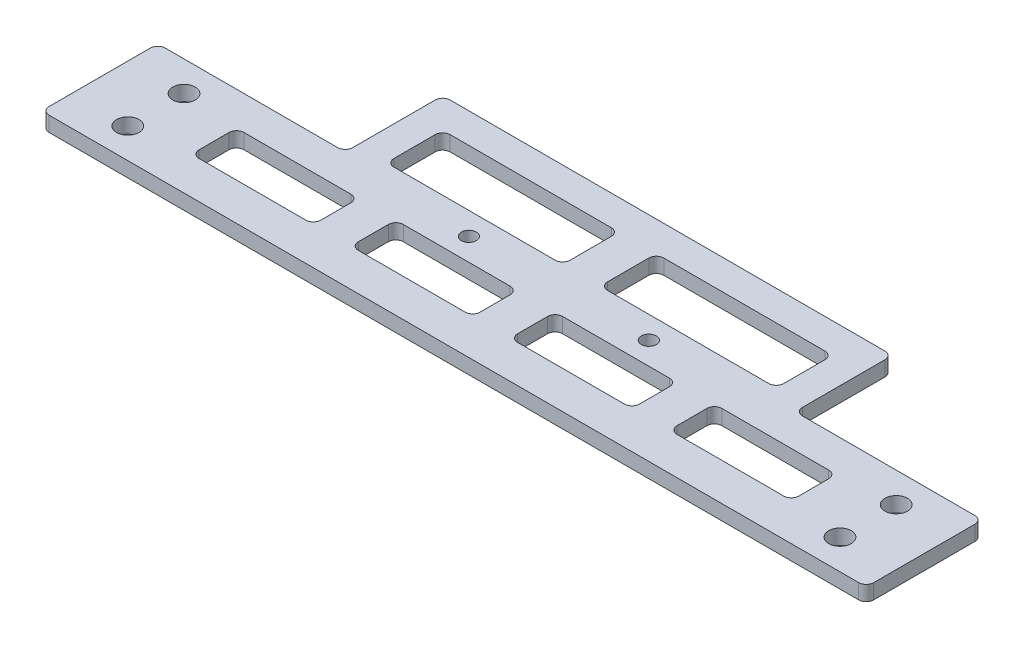
SolidWorks part; units mm, degrees
material "Thornel Mat VMA"
ref_plane "前视基准面" through (0, 0, 0) normal (0, 0, 1) x (1, 0, 0)
ref_plane "上视基准面" through (0, 0, 0) normal (0, 1, 0) x (1, 0, 0)
ref_plane "右视基准面" through (0, 0, 0) normal (1, 0, 0) x (0, 0, -1)
sketch "草图1" plane through (0, 0, 0) normal (0, 1, 0) x (1, 0, 0)
  line L0 (-47.5, 3.75) -> (47.5, -3.75) construction
  line L1 (-47.5, 3.75) -> (47.5, 3.75) construction
  line L2 (-47.5, 3.75) -> (-47.5, -3.75) construction
  line L3 (-47.5, -3.75) -> (47.5, -3.75) construction
  line L4 (47.5, 3.75) -> (47.5, -3.75) construction
  line L5 (30, 7.75) -> (55, 7.75)
  line L6 (-55, 7.75) -> (-30, 7.75)
  line L7 (-55, 7.75) -> (-55, -7.75)
  line L8 (-55, -7.75) -> (55, -7.75)
  line L9 (55, 7.75) -> (55, -7.75)
  line L11 (-30, 7.75) -> (-30, 20.75)
  line L12 (-30, 20.75) -> (30, 20.75)
  line L13 (30, 7.75) -> (30, 20.75)
  line L14 (-12, 6.25) -> (12, 6.25) construction
  line L15 (0, 0) -> (0, 6.25) construction
  circle A0 centre (-47.5, 3.75) radius 1.5
  circle A1 centre (-47.5, -3.75) radius 1.5
  circle A2 centre (47.5, 3.75) radius 1.5
  circle A3 centre (47.5, -3.75) radius 1.5
  circle A4 centre (-12, 6.25) radius 1
  circle A5 centre (12, 6.25) radius 1
  dimension "D5" = 3
  dimension "D11" = 2
  dimension "D1" = 7.5
  dimension "D2" = 95
  dimension "D3" = 7.5
  dimension "D4" = 4
  dimension "D6" = 7.5
  dimension "D7" = 60
  dimension "D8" = 4
  dimension "D9" = 13
  dimension "D10" = 24
  dimension "D12" = 14.5
extrude "凸台-拉伸1" add sketch "草图1" along normal blind 2
sketch "草图2" plane through (0, 2, 0) normal (0, 1, 0) x (1, 0, 0)
  line L0 (-55, 7.75) -> (-55, -7.75) construction
  line L1 (-40, 3.25) -> (-23.75, 3.25)
  line L2 (-40, 3.25) -> (-40, -2.75)
  line L3 (-40, -2.75) -> (-23.75, -2.75)
  line L4 (-23.75, 3.25) -> (-23.75, -2.75)
  line L5 (-18.75, 3.25) -> (-2.5, 3.25)
  line L6 (-18.75, 3.25) -> (-18.75, -2.75)
  line L7 (-18.75, -2.75) -> (-2.5, -2.75)
  line L8 (-2.5, 3.25) -> (-2.5, -2.75)
  line L10 (-55, -7.75) -> (55, -7.75) construction
  line L11 (-23.75, -2.75) -> (-18.75, -2.75) construction
  line L12 (-2.5, -2.75) -> (2.5, -2.75) construction
  line L13 (0, -1.1) -> (0, 1.1) construction
  line L14 (-30, 20.75) -> (-30, 7.75) construction
  line L15 (2.5, 3.25) -> (2.5, -2.75)
  line L16 (18.75, -2.75) -> (2.5, -2.75)
  line L17 (18.75, 3.25) -> (18.75, -2.75)
  line L18 (18.75, 3.25) -> (2.5, 3.25)
  line L19 (23.75, 3.25) -> (23.75, -2.75)
  line L20 (40, -2.75) -> (23.75, -2.75)
  line L21 (40, 3.25) -> (40, -2.75)
  line L22 (40, 3.25) -> (23.75, 3.25)
  line L23 (-26, 16.75) -> (-2.5, 16.75)
  line L24 (-26, 16.75) -> (-26, 9.25)
  line L25 (-26, 9.25) -> (-2.5, 9.25)
  line L26 (-2.5, 16.75) -> (-2.5, 9.25)
  line L27 (30, 20.75) -> (-30, 20.75) construction
  line L28 (2.5, 16.75) -> (2.5, 9.25)
  line L29 (26, 9.25) -> (2.5, 9.25)
  line L30 (26, 16.75) -> (26, 9.25)
  line L31 (26, 16.75) -> (2.5, 16.75)
  circle A0 centre (-12, 6.25) radius 1 construction
  dimension "D7" = 3
  dimension "D2" = 3
  dimension "D1" = 15
  dimension "D3" = 5
  dimension "D4" = 5
  dimension "D5" = 4
  dimension "D6" = 4
extrude "切除-拉伸1" cut sketch "草图2" against normal through all
fillet "圆角1" radius 1 32 edges at (-55, 1, 7.75) (55, 1, 7.75) (-55, 1, -7.75) (-2.5, 1, -3.25) (-2.5, 1, 2.75) (-18.75, 1, 2.75) (-18.75, 1, -3.25) (23.75, 1, -3.25) (40, 1, -3.25) (40, 1, 2.75) (23.75, 1, 2.75) (2.5, 1, 2.75) (2.5, 1, -3.25) (18.75, 1, -3.25) (18.75, 1, 2.75) (-23.75, 1, 2.75) (-40, 1, 2.75) (-23.75, 1, -3.25) (-40, 1, -3.25) (-30, 1, -7.75) (30, 1, -20.75) (30, 1, -7.75) (55, 1, -7.75) (-30, 1, -20.75) (26, 1, -9.25) (2.5, 1, -9.25) (2.5, 1, -16.75) (26, 1, -16.75) (-2.5, 1, -16.75) (-2.5, 1, -9.25) (-26, 1, -16.75) (-26, 1, -9.25)
